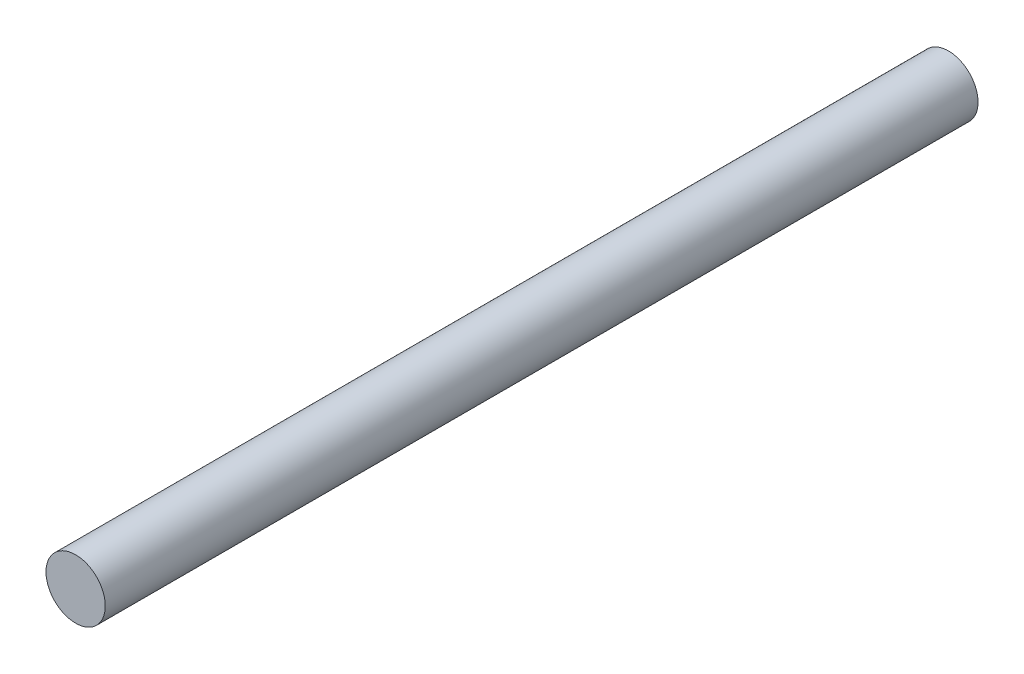
SolidWorks part; units mm, degrees
ref_plane "Front Plane" through (0, 0, 0) normal (0, 0, 1) x (1, 0, 0)
ref_plane "Top Plane" through (0, 0, 0) normal (0, 1, 0) x (1, 0, 0)
ref_plane "Right Plane" through (0, 0, 0) normal (1, 0, 0) x (0, 0, -1)
sketch "Sketch1" plane through (0, 0, 0) normal (0, 0, 1) x (1, 0, 0)
  circle A0 centre (0, 0) radius 3.9688
  dimension "D1" = 7.9375
extrude "Extrude1" add sketch "Sketch1" along normal mid plane 116.84
